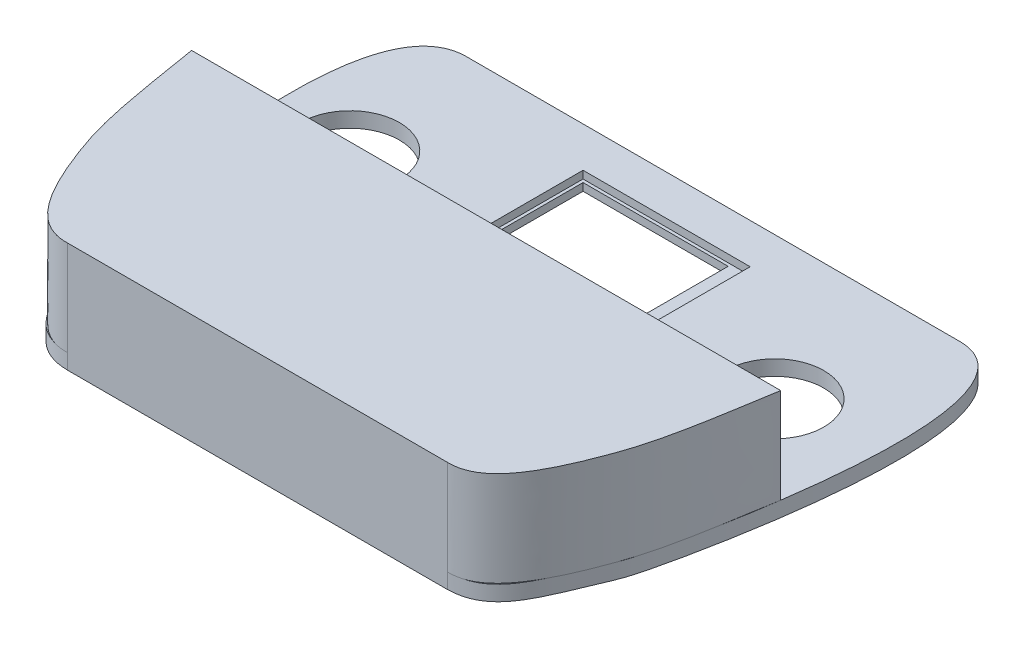
SolidWorks part; units mm, degrees
ref_plane "Front Plane" through (0, 0, 0) normal (0, 0, 1) x (1, 0, 0)
ref_plane "Top Plane" through (0, 0, 0) normal (0, 1, 0) x (1, 0, 0)
ref_plane "Right Plane" through (0, 0, 0) normal (1, 0, 0) x (0, 0, -1)
sketch "Sketch1" plane through (0, 0, 0) normal (0, 1, 0) x (1, 0, 0)
  line L0 (0, 59.7647) -> (0, -60.2353) construction
  line L1 (-65, 59.7647) -> (65, 59.7647)
  line L2 (-50, -60.2353) -> (50, -60.2353)
  spline S0 degree 3 poles (-65, 59.7647) (-88.6877, 59.7145) (-73.4222, -28.0966) (-64.1791, -48.9806) (-61.1512, -60.0099) (-50, -60.2353) knots 0 0 0 0 0.225756 0.325756 1 1 1 1
  spline S1 degree 3 poles (65, 59.7647) (88.6877, 59.7145) (73.4222, -28.0966) (64.1791, -48.9806) (61.1512, -60.0099) (50, -60.2353) knots 0 0 0 0 0.225756 0.325756 1 1 1 1
  point P3 (0, 32.2647)
  dimension "D1" = 65
  dimension "D2" = 120
  dimension "D3" = 100
  dimension "D4" = 50
  dimension "D5" = 120
extrude "Boss-Extrude1" add sketch "Sketch1" along normal blind 4
sketch "Sketch3" plane through (0, 0, 0) normal (0, -1, 0) x (-1, 0, 0)
  line L0 (0, 59.7183) -> (0, -60.0732) construction
  circle A0 centre (-53.6457, 22.3397) radius 12.9003
  circle A2 centre (58.7592, 22.9147) radius 13
  dimension "D1" = 25.8006
  dimension "D2" = 26
extrude "Cut-Extrude2" cut sketch "Sketch3" against normal through all contours A2 | A0
sketch "Sketch6" plane through (0, 4, 0) normal (0, -1, 0) x (-1, 0, 0)
  line L0 (-65, 59.7647) -> (65, 59.7647) construction
  line L1 (-20.3, 49.2047) -> (23.7, 49.2047)
  line L2 (-20.3, 49.2047) -> (-20.3, 15.2047)
  line L3 (-20.3, 15.2047) -> (23.7, 15.2047)
  line L4 (23.7, 49.2047) -> (23.7, 15.2047)
  line L5 (-20.3, 49.2047) -> (23.7, 15.2047) construction
  line L6 (-20.3, 15.2047) -> (23.7, 49.2047) construction
  line L7 (0, 15.95) -> (0, -15.95) construction
  point P0 (1.7, 32.2047)
  dimension "D1" = 10.56
  dimension "D2" = 34
  dimension "D3" = 44
  dimension "D4" = 1.7
extrude "Cut-Extrude3" cut sketch "Sketch6" along normal blind 2
sketch "Sketch8" plane through (0, 2, 0) normal (0, 1, 0) x (1, 0, 0)
  line L0 (15.3, 48.4047) -> (15.3, 16.0047)
  line L1 (-23.7, 49.2047) -> (20.3, 49.2047) construction
  line L2 (20.3, 15.2047) -> (-23.7, 15.2047) construction
  line L3 (20.3, 49.2047) -> (20.3, 15.2047) construction
  line L4 (15.3, 48.4047) -> (-22.9, 48.4047)
  line L6 (-22.9, 16.0047) -> (15.3, 16.0047)
  line L7 (-22.9, 48.4047) -> (-22.9, 16.0047)
  line L10 (-23.7, 15.2047) -> (-23.7, 49.2047) construction
  dimension "D1" = 5
  dimension "D2" = 0.8
  dimension "D3" = 0.8
  dimension "D4" = 0.8
extrude "Cut-Extrude5" cut sketch "Sketch8" against normal through all
sketch "Sketch10" plane through (0, 4, 0) normal (0, 1, 0) x (1, 0, 0)
  line L0 (-50, -60.2353) -> (50, -60.2353)
  line L1 (-77.5396, 0) -> (77.5396, 0)
  line L2 (0, 0) -> (0, -60.2353) construction
  spline S0 degree 3 poles (50, -60.2353) (61.1512, -60.0099) (64.1791, -48.9806) (73.4222, -28.0966) (88.6877, 59.7145) (65, 59.7647) knots 0 0 0 0 0.674244 0.774244 1 1 1 1 construction
  spline S1 degree 3 poles (-65, 59.7647) (-88.6877, 59.7145) (-73.4222, -28.0966) (-64.1791, -48.9806) (-61.1512, -60.0099) (-50, -60.2353) knots 0 0 0 0 0.225756 0.325756 1 1 1 1 construction
  spline S2 degree 3 poles (-77.5396, 0) (-76.4117, -6.47) (-73.8615, -24.6314) (-64.1387, -53.2137) (-57.4303, -60.4265) (-50, -60.2353) knots 0 0 0 0 0.260174 0.360174 1 1 1 1
  spline S3 degree 3 poles (77.5396, 0) (76.4117, -6.47) (73.8615, -24.6314) (64.1387, -53.2137) (57.4303, -60.4265) (50, -60.2353) knots 0 0 0 0 0.260174 0.360174 1 1 1 1
extrude "Boss-Extrude2" add sketch "Sketch10" along normal blind 25
